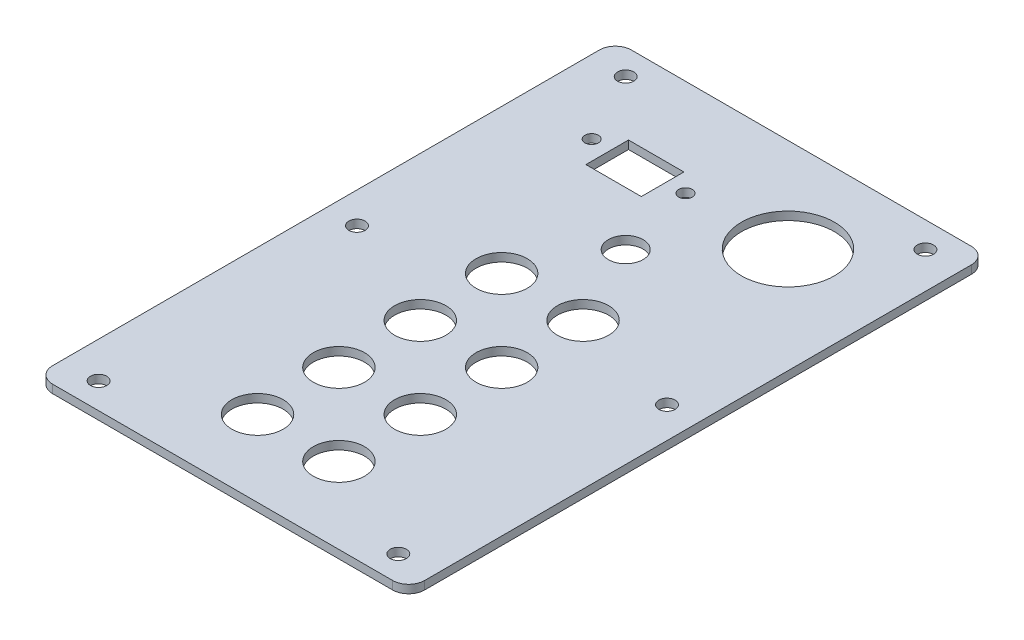
SolidWorks part; units mm, degrees
ref_plane "Front Plane" through (0, 0, 0) normal (0, 0, 1) x (1, 0, 0)
ref_plane "Top Plane" through (0, 0, 0) normal (0, 1, 0) x (1, 0, 0)
ref_plane "Right Plane" through (0, 0, 0) normal (1, 0, 0) x (0, 0, -1)
sketch "Sketch1" plane through (0, 0, 0) normal (0, 1, 0) x (1, 0, 0)
  line L2 (-41.275, 92.3082) -> (41.275, 92.3082) construction
  line L3 (-41.275, 92.3082) -> (-41.275, -66.4418) construction
  line L4 (-41.275, -66.4418) -> (41.275, -66.4418) construction
  line L5 (41.275, 92.3082) -> (41.275, -66.4418) construction
  line L22 (0, -75.9668) -> (0, 101.8332) construction
  line L31 (-57.15, -75.9668) -> (57.15, -75.9668)
  line L32 (-57.15, -75.9668) -> (-57.15, 101.8332)
  line L33 (-57.15, 101.8332) -> (57.15, 101.8332)
  line L34 (57.15, -75.9668) -> (57.15, 101.8332)
  line L48 (-2.7791, 72.0353) -> (-36.5852, 72.0353) construction
  line L49 (-11.7075, 64.3667) -> (-28.7255, 64.3667)
  line L50 (-11.7075, 64.3667) -> (-11.7075, 77.4477)
  line L51 (-11.7075, 77.4477) -> (-28.7255, 77.4477)
  line L52 (-28.7255, 64.3667) -> (-28.7255, 77.4477)
  circle A5 centre (-12.7, 22.4582) radius 7.874
  circle A8 centre (0, 47.8582) radius 5.334
  circle A9 centre (24.765, 72.9407) radius 14.2875
  circle A10 centre (-46.0375, -68.0293) radius 2.4892
  circle A11 centre (-46.0375, 93.8957) radius 2.4892
  circle A12 centre (-47.625, 12.9332) radius 2.4892
  circle A13 centre (46.0375, 93.8957) radius 2.4892
  circle A14 centre (47.625, 12.9332) radius 2.4892
  circle A15 centre (46.0375, -68.0293) radius 2.4892
  circle A25 centre (-5.802, 72.0353) radius 2.0638
  circle A26 centre (-34.631, 72.0353) radius 2.0638
  circle A27 centre (12.3, 22.4582) radius 7.874
  circle A28 centre (12.3, -2.5418) radius 7.874
  circle A29 centre (12.3, -27.5418) radius 7.874
  circle A30 centre (12.3, -52.5418) radius 7.874
  circle A31 centre (-12.7, -2.5418) radius 7.874
  circle A32 centre (-12.7, -27.5418) radius 7.874
  circle A33 centre (-12.7, -52.5418) radius 7.874
  point P54 (67.913, -64.5113)
  point P67 (57.15, -75.9668)
  dimension "D36" = 4.9784
  dimension "D37" = 4.9784
  dimension "D40" = 4.9784
  dimension "D20" = 28.575
  dimension "D9" = 15.748
  dimension "D2" = 82.55
  dimension "D3" = 69.85
  dimension "D4" = 28.575
  dimension "D5" = 19.3675
  dimension "D6" = 13.081
  dimension "D7" = 28.829
  dimension "D8" = 5.9055
  dimension "D10" = 17.018
  dimension "D11" = 7.6686
  dimension "D12" = 2
  dimension "D13" = 4
  dimension "D16" = 16.51
  dimension "D17" = 41.275
  dimension "D19" = 44.45
  dimension "D21" = 177.8
  dimension "D22" = 114.3
  dimension "D23" = 15.875
  dimension "D24" = 158.75
  dimension "D33" = 9.525
  dimension "D34" = 11.1125
  dimension "D35" = 7.9375
  dimension "D38" = 11.1125
  dimension "D39" = 7.9375
  dimension "D41" = 9.525
  dimension "D42" = 88.9
extrude "Boss-Extrude1" add sketch "Sketch1" along normal blind 2.54
fillet "Fillet1" radius 4.92 4 edges at (57.15, 1.27, 75.9668) (57.15, 1.27, -101.8332) (-57.15, 1.27, -101.8332) (-57.15, 1.27, 75.9668)
sketch "Sketch2" plane through (0, 2.54, 0) normal (0, 1, 0) x (1, 0, 0)
  point P0 (57.15, -75.9668)
